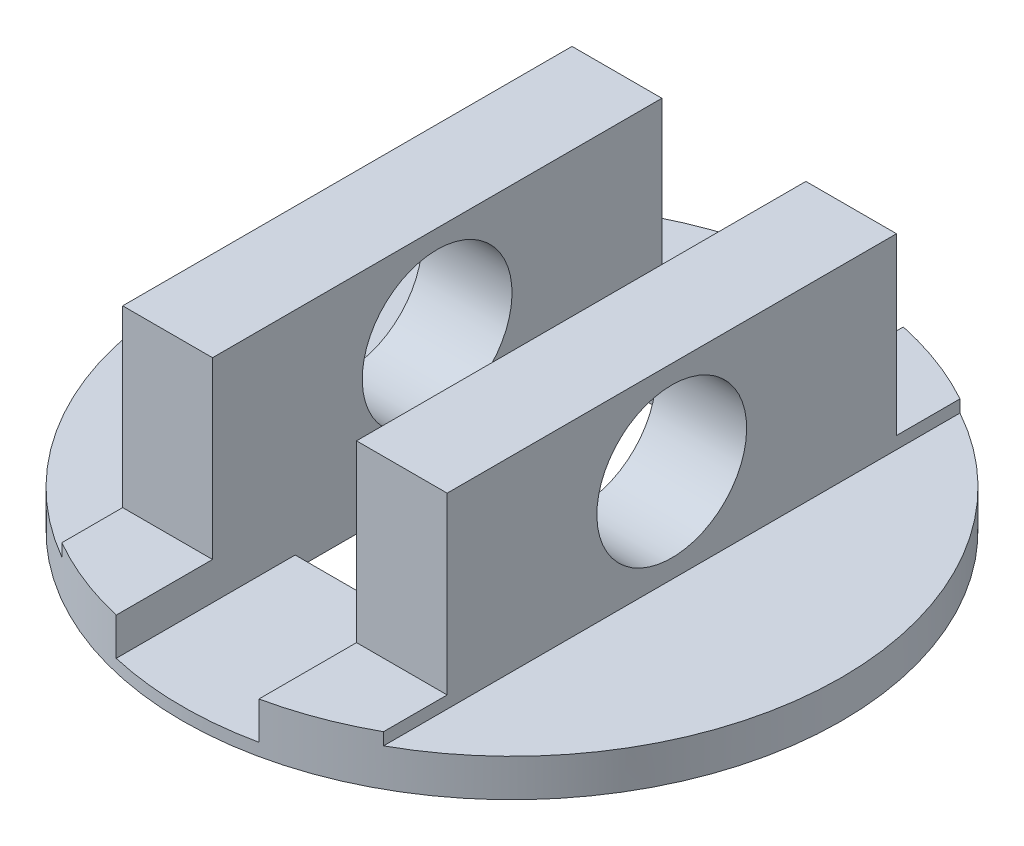
SolidWorks part; units mm, degrees
ref_plane "Front Plane" through (0, 0, 0) normal (0, 0, 1) x (1, 0, 0)
ref_plane "Top Plane" through (0, 0, 0) normal (0, 1, 0) x (1, 0, 0)
ref_plane "Right Plane" through (0, 0, 0) normal (1, 0, 0) x (0, 0, -1)
sketch "Sketch2" plane through (0, 0, 0) normal (0, 1, 0) x (1, 0, 0)
  circle A0 centre (0, 0) radius 132
extrude "Boss-Extrude1" add sketch "Sketch2" along normal blind 90
sketch "Sketch3" plane through (0, 0, 0) normal (0, 0, 1) x (1, 0, 0)
  line L0 (0, 0) -> (0, 90) construction
  line L1 (132, 90) -> (-132, 90) construction
  line L2 (0, 90) -> (-30, 90)
  line L3 (0, 90) -> (30, 90)
  line L5 (-30, 90) -> (27.6794, 90)
  line L6 (-30, 90) -> (-30, 5)
  line L7 (-30, 5) -> (27.6794, 5)
  line L8 (27.6794, 90) -> (27.6794, 5)
  point P8 (30, 90)
  dimension "D1" = 85
extrude "Cut-Extrude1" cut sketch "Sketch3" against normal mid plane 320 contours L5 L8 L7 L6
sketch "Sketch4" plane through (0, 0, 0) normal (0, 0, 1) x (1, 0, 0)
  line L0 (-30, 90) -> (-66, 90)
  line L1 (-30, 90) -> (-132, 90) construction
  line L2 (27.6794, 90) -> (63.982, 90)
  line L3 (132, 90) -> (27.6794, 90) construction
  line L4 (-30, 5) -> (-30, 15)
  line L5 (-30, 5) -> (-30, 90) construction
  line L6 (-132, 90) -> (-132, 0) construction
  line L7 (-66, 90) -> (-132, 90)
  line L8 (-66, 90) -> (-66, 15)
  line L9 (-66, 15) -> (-132, 15)
  line L10 (-132, 90) -> (-132, 15)
  line L12 (63.982, 90) -> (133.8558, 90)
  line L13 (63.982, 90) -> (63.982, 15.0746)
  line L14 (63.982, 15.0746) -> (133.8558, 15.0746)
  line L15 (133.8558, 90) -> (133.8558, 15.0746)
extrude "Cut-Extrude2" cut sketch "Sketch4" against normal mid plane 320 contours L7 L10 L9 L8 | L12 L15 L14 L13
sketch "Sketch5" plane through (63.982, 0, 0) normal (1, 0, 0) x (0, 0, -1)
  line L0 (0, 90) -> (0, 15.0746) construction
  line L1 (115.4569, 90) -> (-115.4569, 90) construction
  line L2 (115.4569, 15.0746) -> (-115.4569, 15.0746) construction
  circle A0 centre (0, 52.5373) radius 30
extrude "Cut-Extrude3" cut sketch "Sketch5" against normal mid plane 320
sketch "Sketch6" plane through (0, 5, 0) normal (0, 1, 0) x (1, 0, 0)
  line L0 (-30, 128.5457) -> (-30, -128.5457) construction
  line L1 (-30, 71.7901) -> (27.6794, 71.7901)
  line L2 (-30, 71.7901) -> (-30, -56.8649)
  line L3 (-30, -56.8649) -> (27.6794, -56.8649)
  line L4 (27.6794, 71.7901) -> (27.6794, -56.8649)
  line L5 (27.6794, 129.0653) -> (27.6794, -129.0653) construction
extrude "Cut-Extrude4" cut sketch "Sketch6" against normal mid plane 320
sketch "Sketch7" plane through (0, 90, 0) normal (0, 1, 0) x (1, 0, 0)
  line L5 (-73.0949, 90.0396) -> (70.2397, 90.0396)
  line L6 (-73.0949, 90.0396) -> (-73.0949, -89.9604)
  line L7 (-73.0949, -89.9604) -> (70.2397, -89.9604)
  line L8 (70.2397, 90.0396) -> (70.2397, -89.9604)
  line L9 (-105.5881, 135.8945) -> (96.6594, 135.8945)
  line L10 (-105.5881, 135.8945) -> (-105.5881, -141.3607)
  line L11 (-105.5881, -141.3607) -> (96.6594, -141.3607)
  line L12 (96.6594, 135.8945) -> (96.6594, -141.3607)
  point P12 (-30, 0.0396)
extrude "Cut-Extrude5" cut sketch "Sketch7" against normal mid plane 140
